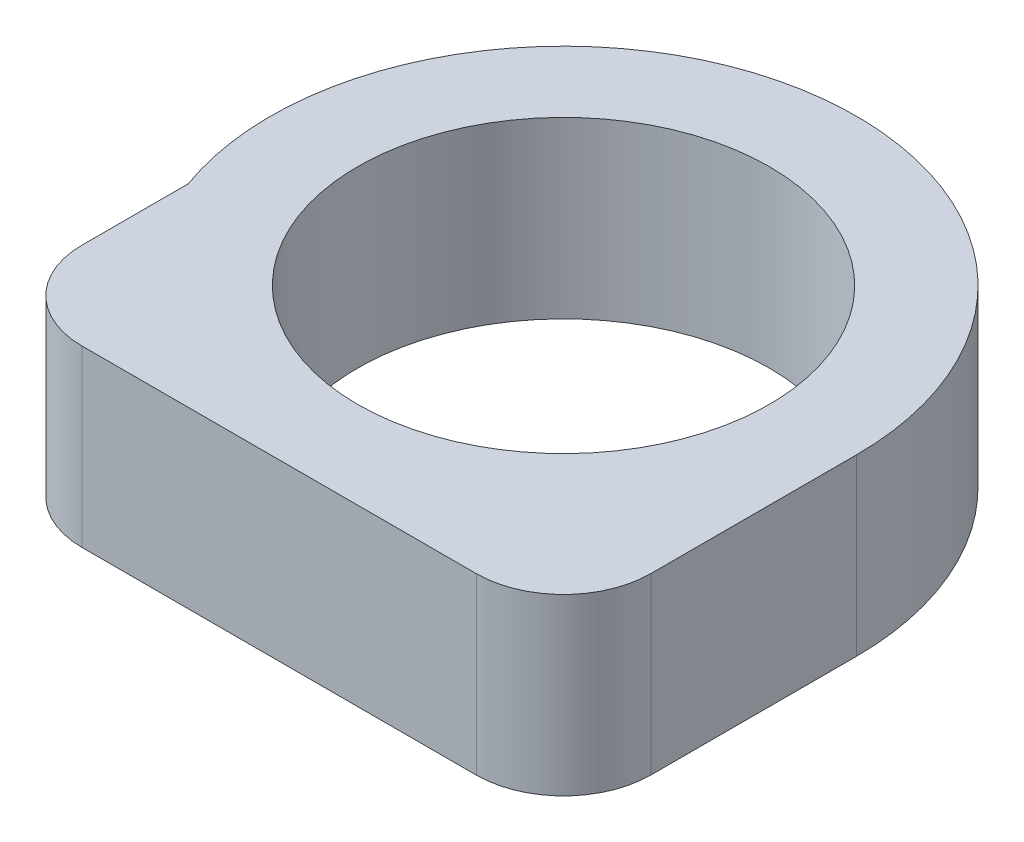
SolidWorks part; units mm, degrees
ref_plane "Front Plane" through (0, 0, 0) normal (0, 0, 1) x (1, 0, 0)
ref_plane "Top Plane" through (0, 0, 0) normal (0, 1, 0) x (1, 0, 0)
ref_plane "Right Plane" through (0, 0, 0) normal (1, 0, 0) x (0, 0, -1)
sketch "Sketch1" plane through (0, 0, 0) normal (0, 1, 0) x (1, 0, 0)
  line L1 (-18.5125, 1.616) -> (14.0875, 1.616)
  line L2 (-18.5125, 1.616) -> (-18.5125, -15.184)
  line L3 (-18.5125, -15.184) -> (14.0875, -15.184)
  line L4 (14.0875, 1.616) -> (14.0875, -15.184)
  circle A0 centre (-2.7125, 1.616) radius 11.8
  circle A1 centre (-2.7125, 1.616) radius 16.8
  dimension "D1" = 23.6
  dimension "D2" = 5
  dimension "D3" = 0
  dimension "D4" = 15.8
  dimension "D5" = 16.8
  dimension "D6" = 16.8
extrude "Boss-Extrude2" add sketch "Sketch1" along normal blind 10 contours A1 L1 A0 | L1 A1 A0 | A1 L3 L4 | A1 L2 L3
fillet "Fillet1" radius 5 2 edges at (-18.5125, 5, 15.184) (14.0875, 5, 15.184)
equation "\"w1\"= ( 21.68 + 21.52 ) / 2"
equation "\"w2\"= ( 19.35 + 19.57 ) / 2"
equation "\"w3\"= 17.03"
equation "\"w4\"= ( 15.09 + 15.18 ) / 2"
equation "\"w5\"= 13.2"
equation "\"w6\"= ( 11.13 + 11.42 ) / 2"
equation "\"w7\"= 9.3"
equation "\"mount_height\" = 20"
equation "\"mount_thickness\"= 5"
equation "\"D1@Sketch1\" = \"w1\" + \"tolerance\""
equation "\"D2@Sketch1\"=\"mount_thickness\""
equation "\"webcam depth\"= 40.4"
equation "\"D6@Sketch1\"=\"D1@Sketch1\"/2+\"D2@Sketch1\""
equation "\"D5@Sketch1\"=\"D6@Sketch1\""
equation "\"tolerance\"= 2"
